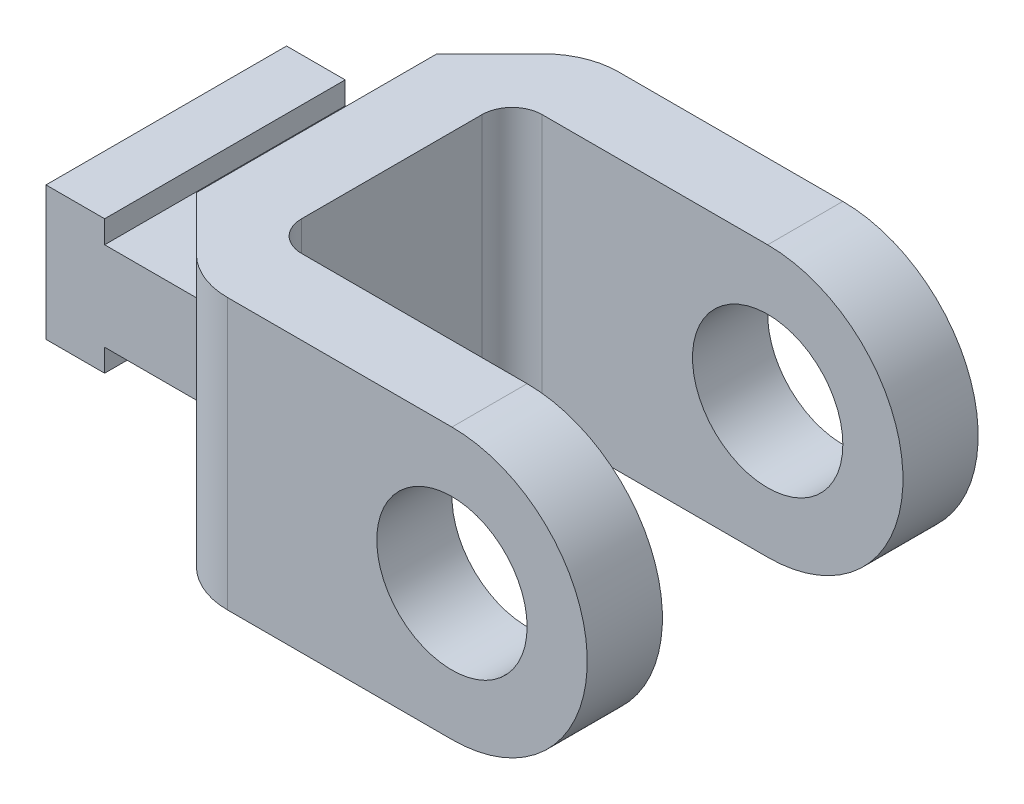
SolidWorks part; units mm, degrees
ref_plane "Front Plane" through (0, 0, 0) normal (0, 0, 1) x (1, 0, 0)
ref_plane "Top Plane" through (0, 0, 0) normal (0, 1, 0) x (1, 0, 0)
ref_plane "Right Plane" through (0, 0, 0) normal (1, 0, 0) x (0, 0, -1)
sketch "Sketch1" plane through (0, 0, 0) normal (0, 0, 1) x (1, 0, 0)
  line L0 (-8.6486, 0) -> (8.2152, 0) construction
  line L22 (1.25, -4.5) -> (-1.25, -4.5)
  line L23 (-1.25, 4.5) -> (-1.25, 1.475)
  line L25 (1.25, -4.5) -> (1.25, 4.5)
  line L26 (1.25, 4.5) -> (-1.25, 4.5)
  line L28 (1.25, -4.5) -> (-1.25, 4.5) construction
  line L29 (1.25, 4.5) -> (-1.25, -4.5) construction
  line L32 (-6.25, -2.225) -> (-4.3, -2.225)
  line L33 (-6.25, -2.225) -> (-6.25, 2.225)
  line L34 (-6.25, 2.225) -> (-4.3, 2.225)
  line L35 (-4.3, -2.225) -> (-4.3, -1.475)
  line L36 (-6.25, -2.225) -> (-4.3, 2.225) construction
  line L37 (-6.25, 2.225) -> (-4.3, -2.225) construction
  line L38 (-4.3, 1.475) -> (-4.3, 2.225)
  line L39 (-4.3, -1.475) -> (-1.25, -1.475)
  line L41 (-4.3, 1.475) -> (-1.25, 1.475)
  line L43 (-4.3, -1.475) -> (-1.25, 1.475) construction
  line L44 (-4.3, 1.475) -> (-1.25, -1.475) construction
  line L45 (-1.25, -1.475) -> (-1.25, -4.5)
  point P0 (0, 0)
  point P3 (0, 0)
  point P6 (1.5718, 1.475)
  point P8 (-5.275, 0)
  point P9 (1.5718, -1.475)
  point P12 (-2.775, 0)
  dimension "D1" = 3.05
  dimension "D2" = 2.5
  dimension "D3" = 9
  dimension "D4" = 2.95
  dimension "D5" = 4.45
  dimension "D6" = 1.95
extrude "Boss-Extrude1" add sketch "Sketch1" along normal blind 8 contours L26 L23 L41 L38 L34 L33 L32 L35 L39 L45 L22 L25
sketch "Sketch2" plane through (0, 0, 0) normal (0, 0, 1) x (1, 0, 0)
  line L0 (-4.6464, 0) -> (18.6847, 0) construction
  line L3 (9.75, -4.5) -> (-1.25, -4.5)
  line L5 (9.75, 4.5) -> (-1.25, 4.5)
  line L6 (-1.25, -4.5) -> (-1.25, 4.5)
  line L7 (12.7356, -3.3669) -> (-1.25, 4.5) construction
  line L8 (12.7356, 3.3669) -> (-1.25, -4.5) construction
  line L11 (-1.25, 4.5) -> (-1.25, 1.475) construction
  arc A0 (9.75, -4.5) -> (9.75, 4.5) centre (9.75, 0) ccw
  circle A1 centre (9.75, 0) radius 2.5
  circle A2 centre (9.75, 0) radius 7.5 construction
  point P5 (6.75, 0)
  point P7 (14.25, 0)
  dimension "D3" = 5
  dimension "D4" = 15
  dimension "D1" = 15.5
  dimension "D2" = 9
extrude "Boss-Extrude3" add sketch "Sketch2" against normal blind 2.5
sketch "Sketch5" plane through (0, 4.5, 0) normal (0, 1, 0) x (1, 0, 0)
  line L0 (1.25, 0) -> (1.25, 4.091) construction
  line L1 (9.75, 2.5) -> (-1.25, 2.5) construction
  line L6 (-1.25, 2.5) -> (1.25, 2.5)
  line L7 (-1.25, 2.5) -> (-1.25, 0)
  line L8 (-1.25, 0) -> (1.25, 2.5)
  point P3 (1.25, 2.5)
  point P8 (-1.25, 0)
extrude "Cut-Extrude2" cut sketch "Sketch5" against normal through all and the other way through all
fillet "Fillet5" radius 1 1 edges at (1.25, 0, 0)
fillet "Fillet6" radius 2.5 1 edges at (1.25, 0, -2.5)
ref_plane "Plane1" through (0, 0, 4) normal (0, 0, -1) x (-1, 0, 0)
mirror "Mirror2" about plane through (0, 0, 4) normal (0, 0, -1) of "Cut-Extrude2", "Fillet6", "Fillet5", "Boss-Extrude3"
